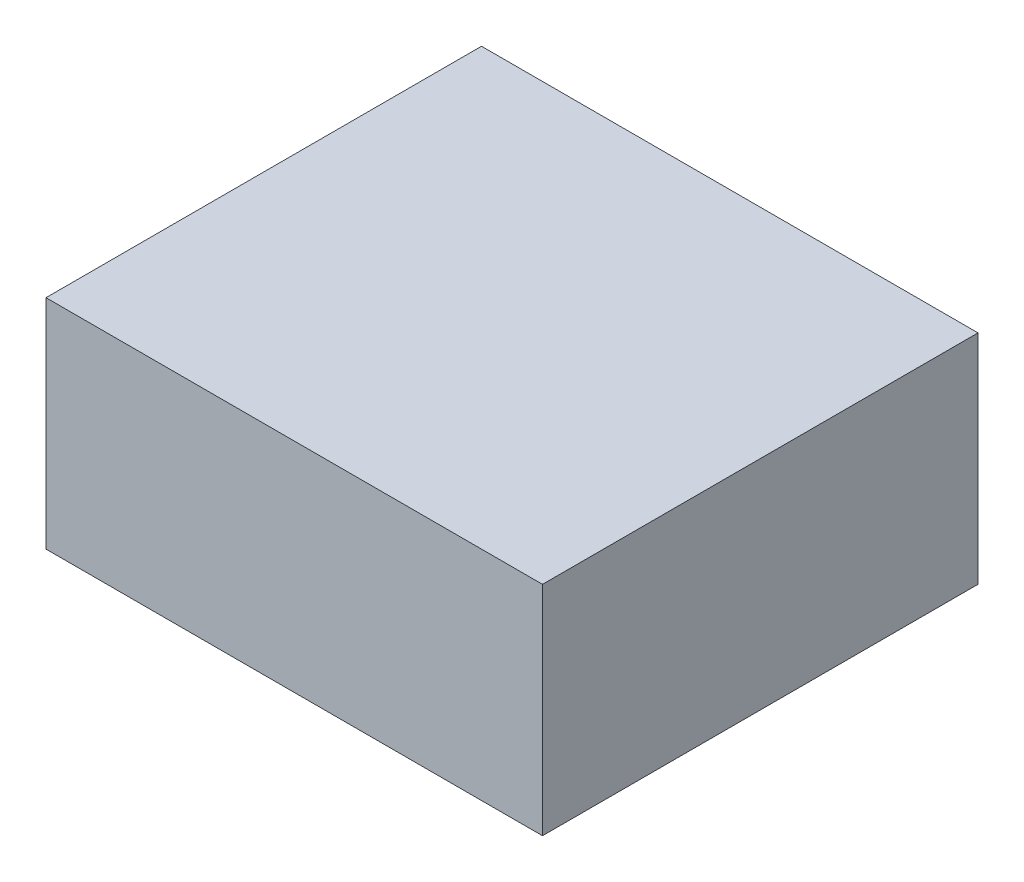
SolidWorks part; units mm, degrees
ref_plane "Front Plane" through (0, 0, 0) normal (0, 0, 1) x (1, 0, 0)
ref_plane "Top Plane" through (0, 0, 0) normal (0, 1, 0) x (1, 0, 0)
ref_plane "Right Plane" through (0, 0, 0) normal (1, 0, 0) x (0, 0, -1)
sketch "Sketch1" plane through (0, 0, 0) normal (0, 1, 0) x (1, 0, 0)
  line L1 (-2.85, 2.5) -> (2.85, 2.5)
  line L2 (-2.85, 2.5) -> (-2.85, -2.5)
  line L3 (-2.85, -2.5) -> (2.85, -2.5)
  line L4 (2.85, 2.5) -> (2.85, -2.5)
  line L5 (-2.85, 2.5) -> (2.85, -2.5) construction
  line L6 (-2.85, -2.5) -> (2.85, 2.5) construction
  point P0 (0, 0)
  dimension "D1" = 5.7
  dimension "D2" = 5
extrude "Boss-Extrude1" add sketch "Sketch1" along normal blind 2.5
